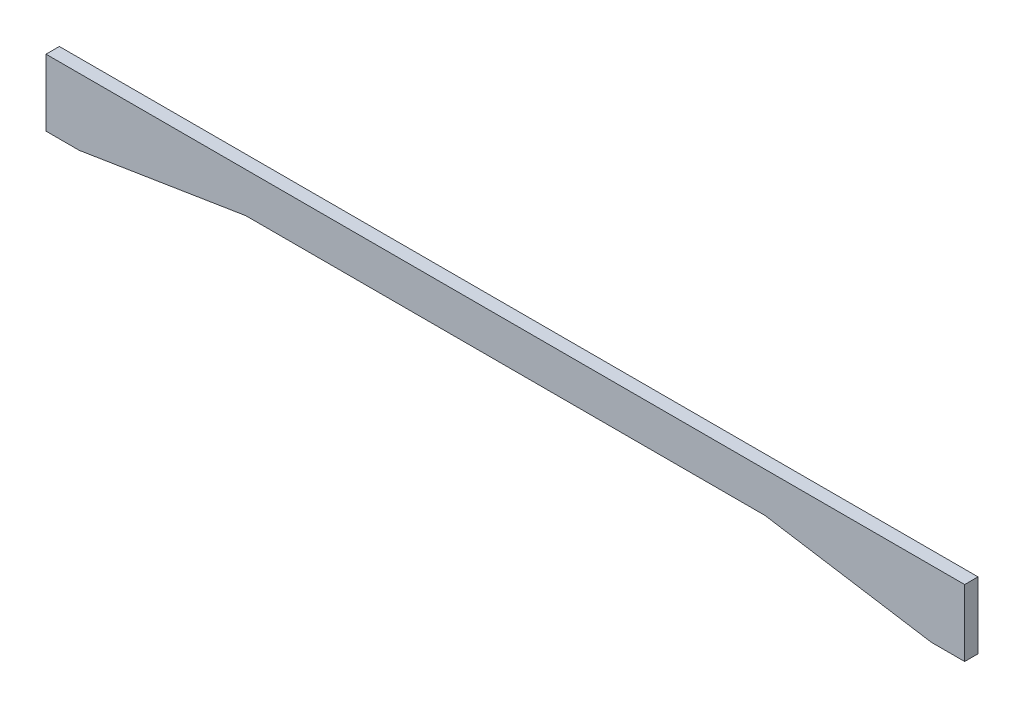
SolidWorks part; units mm, degrees
ref_plane "Front Plane" through (0, 0, 0) normal (0, 0, 1) x (1, 0, 0)
ref_plane "Top Plane" through (0, 0, 0) normal (0, 1, 0) x (1, 0, 0)
ref_plane "Right Plane" through (0, 0, 0) normal (1, 0, 0) x (0, 0, -1)
sketch "Sketch1" plane through (0, 0, 0) normal (0, 0, 1) x (1, 0, 0)
  line L0 (0, 0) -> (-77.8522, 0)
  line L1 (-137.75, -8) -> (-127.75, -8)
  line L2 (-137.75, -8) -> (-137.75, 12)
  line L3 (-137.75, 12) -> (0, 12)
  line L4 (0, 12) -> (0, 0)
  line L5 (0, 0) -> (-2.0445, -2.0637)
  line L6 (-127.75, -8) -> (-77.8522, 0)
  dimension "D1" = 137.75
  dimension "D2" = 12
  dimension "D3" = 20
  dimension "D4" = 10
extrude "Boss-Extrude1" add sketch "Sketch1" along normal blind 4
mirror "Mirror1" about plane through (0, 0, 4) normal (1, 0, 0) of "Boss-Extrude1"
